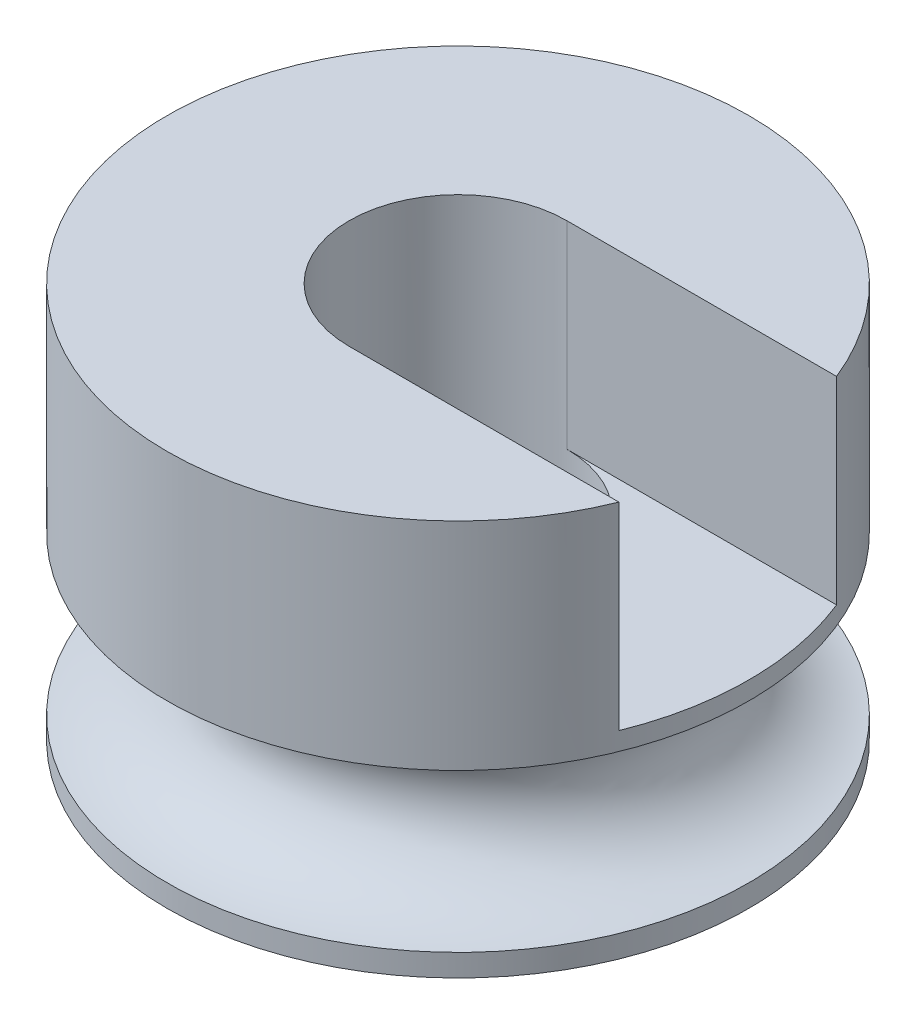
SolidWorks part; units mm, degrees
ref_plane "Front Plane" through (0, 0, 0) normal (0, 0, 1) x (1, 0, 0)
ref_plane "Top Plane" through (0, 0, 0) normal (0, 1, 0) x (1, 0, 0)
ref_plane "Right Plane" through (0, 0, 0) normal (1, 0, 0) x (0, 0, -1)
sketch "Sketch1" plane through (0, 0, 0) normal (0, 1, 0) x (1, 0, 0)
  circle A1 centre (0, 0) radius 7.35
  dimension "D1" = 14.7
extrude "Boss-Extrude1" add sketch "Sketch1" along normal blind 10
sketch "Sketch2" plane through (0, 10, 0) normal (0, 1, 0) x (1, 0, 0)
  line L0 (0, 2.75) -> (9.425, 2.75)
  line L1 (0, -2.75) -> (9.7113, -2.75)
  line L2 (9.7113, -2.75) -> (9.425, 2.75)
  arc A0 (0, 2.75) -> (0, -2.75) centre (0, 0) ccw
  dimension "D1" = 5.5
extrude "Cut-Extrude1" cut sketch "Sketch2" against normal blind 5
sketch "Sketch3" plane through (0, 10, 0) normal (0, 1, 0) x (1, 0, 0)
  circle A0 centre (0, 0) radius 2.75
  arc A1 (0, 2.75) -> (0, -2.75) centre (0, 0) ccw construction
extrude "Cut-Extrude2" cut sketch "Sketch3" against normal through all both and the other way through all
ref_axis "Axis1" through (0, 10, 0) along (0, 1, 0)
sketch "Sketch4" plane through (0, 0, 0) normal (0, 0, 1) x (1, 0, 0)
  ellipse E0 centre (-7.598, 2.5506) end of major axis (-5.098, 2.5506) minor radius 2
  point P0 (-7.598, 2.5506)
  dimension "D1" = 4
  dimension "D2" = 5
revolve "Cut-Revolve1" cut sketch "Sketch4" angle 360 about axis through (0, 10, 0) along (0, 1, 0)
